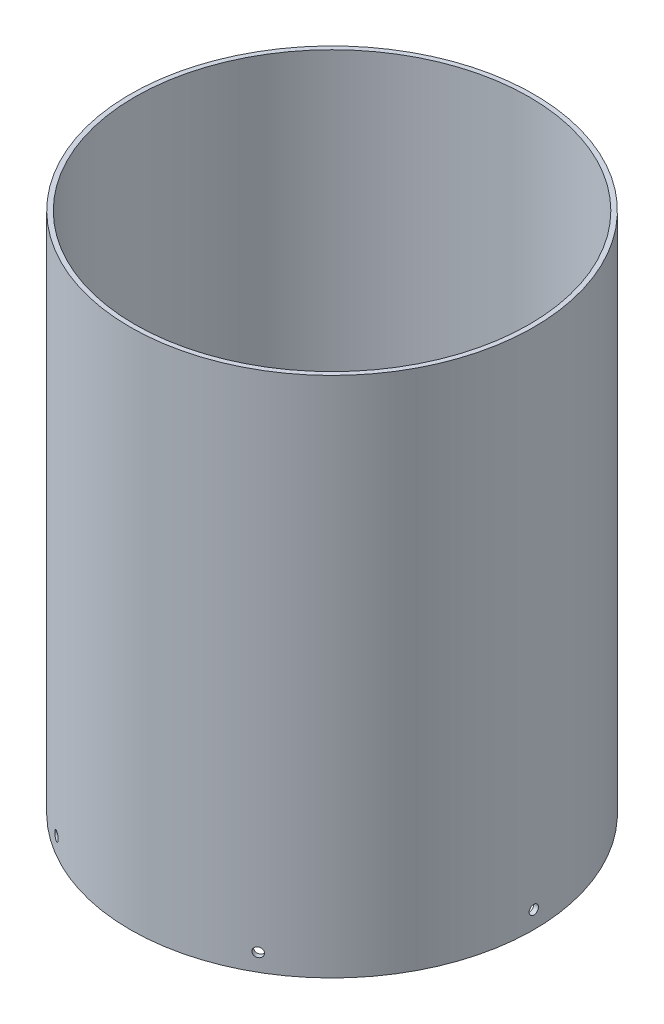
SolidWorks part; units mm, degrees
material "E-Glass Fiber"
ref_plane "Front Plane" through (0, 0, 0) normal (0, 0, 1) x (1, 0, 0)
ref_plane "Top Plane" through (0, 0, 0) normal (0, 1, 0) x (1, 0, 0)
ref_plane "Right Plane" through (0, 0, 0) normal (1, 0, 0) x (0, 0, -1)
sketch "Sketch1" plane through (0, 0, 0) normal (0, 1, 0) x (1, 0, 0)
  circle A0 centre (0, 0) radius 87
  circle A1 centre (0, 0) radius 85
extrude "Boss-Extrude1" add sketch "Sketch1" along normal blind 225
ref_plane "Plane2" through (0, 30, 0) normal (0, -1, 0) x (-1, 0, 0)
ref_plane "Plane1" through (-87, 0, 0) normal (-1, 0, 0) x (0, 0, 1)
sketch "Sketch2" plane through (-87, 0, 0) normal (-1, 0, 0) x (0, 0, 1)
  line L0 (-87, 0) -> (87, 0) construction
  circle A0 centre (0, 7.5) radius 2
  dimension "D1" = 7.5
extrude "Cut-Extrude1" cut sketch "Sketch2" against normal up to next
pattern_circular "CirPattern1" count 6 over 360 about axis through (0, 0, 0) along (0, 1, 0) of "Cut-Extrude1"
